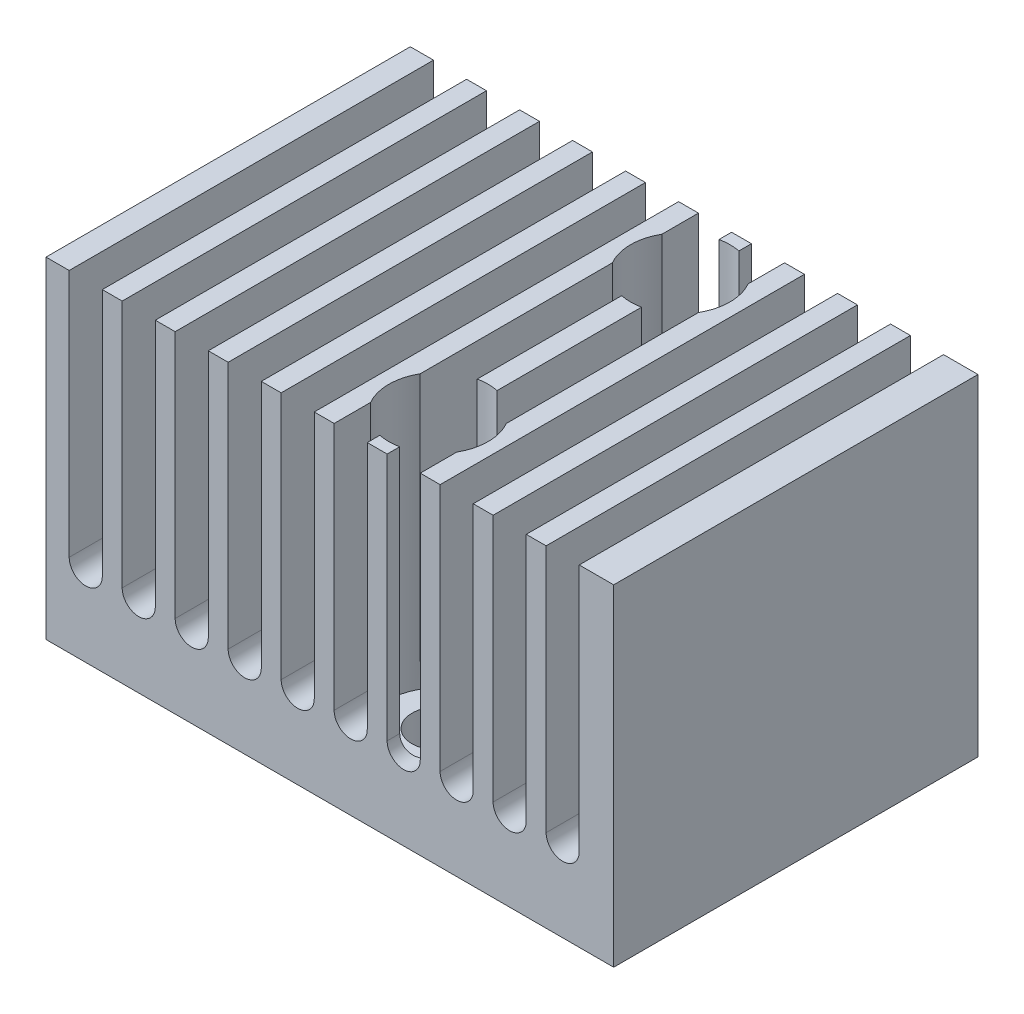
SolidWorks part; units mm, degrees
material "1060 合金"
ref_plane "前视基准面" through (0, 0, 0) normal (0, 0, 1) x (1, 0, 0)
ref_plane "上视基准面" through (0, 0, 0) normal (0, 1, 0) x (1, 0, 0)
ref_plane "右视基准面" through (0, 0, 0) normal (1, 0, 0) x (0, 0, -1)
sketch "草图1" plane through (0, 0, 0) normal (0, 1, 0) x (1, 0, 0)
  line L1 (-8.57, 5.5) -> (8.57, 5.5)
  line L2 (-8.57, 5.5) -> (-8.57, -5.5)
  line L3 (-8.57, -5.5) -> (8.57, -5.5)
  line L4 (8.57, 5.5) -> (8.57, -5.5)
  line L5 (-8.57, 5.5) -> (8.57, -5.5) construction
  line L6 (-8.57, -5.5) -> (8.57, 5.5) construction
  point P0 (0, 0)
  dimension "D1" = 11
  dimension "D2" = 17.14
extrude "凸台-拉伸1" add sketch "草图1" along normal blind 10
sketch "草图2" plane through (0, 0, 5.5) normal (0, 0, 1) x (1, 0, 0)
  line L0 (-8.57, 10) -> (8.57, 10) construction
  line L1 (-7.87, 10) -> (-6.87, 10)
  line L2 (-7.87, 10) -> (-7.87, 2.5)
  line L3 (-7.87, 2.5) -> (-6.87, 2.5)
  line L4 (-6.87, 10) -> (-6.87, 2.5)
  line L5 (-8.57, 10) -> (-8.57, 0) construction
  line L6 (-6.27, 10) -> (-6.27, 2.5)
  line L7 (-6.27, 10) -> (-5.27, 10)
  line L8 (-5.27, 10) -> (-5.27, 2.5)
  line L9 (-6.27, 2.5) -> (-5.27, 2.5)
  line L10 (-4.67, 10) -> (-4.67, 2.5)
  line L11 (-4.67, 10) -> (-3.67, 10)
  line L12 (-3.67, 10) -> (-3.67, 2.5)
  line L13 (-4.67, 2.5) -> (-3.67, 2.5)
  line L14 (-3.07, 10) -> (-3.07, 2.5)
  line L15 (-3.07, 10) -> (-2.07, 10)
  line L16 (-2.07, 10) -> (-2.07, 2.5)
  line L17 (-3.07, 2.5) -> (-2.07, 2.5)
  line L18 (-1.47, 10) -> (-1.47, 2.5)
  line L19 (-1.47, 10) -> (-0.47, 10)
  line L20 (-0.47, 10) -> (-0.47, 2.5)
  line L21 (-1.47, 2.5) -> (-0.47, 2.5)
  line L22 (0.13, 10) -> (0.13, 2.5)
  line L23 (0.13, 10) -> (1.13, 10)
  line L24 (1.13, 10) -> (1.13, 2.5)
  line L25 (0.13, 2.5) -> (1.13, 2.5)
  line L26 (1.73, 10) -> (1.73, 2.5)
  line L27 (1.73, 10) -> (2.73, 10)
  line L28 (2.73, 10) -> (2.73, 2.5)
  line L29 (1.73, 2.5) -> (2.73, 2.5)
  line L30 (3.33, 10) -> (3.33, 2.5)
  line L31 (3.33, 10) -> (4.33, 10)
  line L32 (4.33, 10) -> (4.33, 2.5)
  line L33 (3.33, 2.5) -> (4.33, 2.5)
  line L34 (4.93, 10) -> (4.93, 2.5)
  line L35 (4.93, 10) -> (5.93, 10)
  line L36 (5.93, 10) -> (5.93, 2.5)
  line L37 (4.93, 2.5) -> (5.93, 2.5)
  line L38 (6.53, 10) -> (6.53, 2.5)
  line L39 (6.53, 10) -> (7.53, 10)
  line L40 (7.53, 10) -> (7.53, 2.5)
  line L41 (6.53, 2.5) -> (7.53, 2.5)
  circle A0 centre (-7.37, 2.5) radius 0.5
  circle A1 centre (-5.77, 2.5) radius 0.5
  circle A2 centre (-4.17, 2.5) radius 0.5
  circle A3 centre (-2.57, 2.5) radius 0.5
  circle A4 centre (-0.97, 2.5) radius 0.5
  circle A5 centre (0.63, 2.5) radius 0.5
  circle A6 centre (2.23, 2.5) radius 0.5
  circle A7 centre (3.83, 2.5) radius 0.5
  circle A8 centre (5.43, 2.5) radius 0.5
  circle A9 centre (7.03, 2.5) radius 0.5
  line M8 (8.57, 10) -> (-8.57, 10)
  dimension "D1" = 1
  dimension "D2" = 7.5
  dimension "D3" = 0.7
  dimension "D4" = 10
extrude "切除-拉伸1" cut sketch "草图2" against normal through all contours A0 L4 L2 M8 | A1 L8 L6 M8 | L3 A0 | L3 A0 | L9 A1 | L9 A1 | A2 L12 L10 M8 | L13 A2 | L13 A2 | A3 L16 L14 M8 | L17 A3 | L17 A3 | A4 L20 L18 M8 | L21 A4 | L21 A4 | A5 L24 L22 M8 | L25 A5 | L25 A5 | A6 L28 L26 M8 | L29 A6 | L29 A6 | A7 L32 L30 M8 | L33 A7 | L33 A7 | A8 L36 L34 M8 | L37 A8 | L37 A8 | A9 L40 L38 M8 | L41 A9 | L41 A9
sketch "草图3" plane through (0, 0, 0) normal (0, -1, 0) x (1, 0, 0)
  line L0 (1.43, 5.5) -> (1.43, -5.5)
  line L1 (-8.57, 5.5) -> (8.57, 5.5) construction
  line L2 (8.57, -5.5) -> (-8.57, -5.5) construction
  line L3 (0, 0) -> (11.7843, 0) construction
  line L4 (8.57, 5.5) -> (8.57, -5.5) construction
  circle A0 centre (1.43, 3.65) radius 0.8
  circle A1 centre (1.43, -3.65) radius 0.8
  dimension "D2" = 1.6
  dimension "D1" = 7.14
  dimension "D3" = 3.65
extrude "切除-拉伸2" cut sketch "草图3" against normal blind 1.75 contours L0 A0 | L0 A0 | A1 L0 | A1 L0
sketch "草图4" plane through (0, 1.75, 0) normal (0, -1, 0) x (1, 0, 0)
  circle A0 centre (1.43, 3.65) radius 1.5
  circle A1 centre (1.43, -3.65) radius 1.5
  dimension "D1" = 3
extrude "切除-拉伸3" cut sketch "草图4" against normal through all
